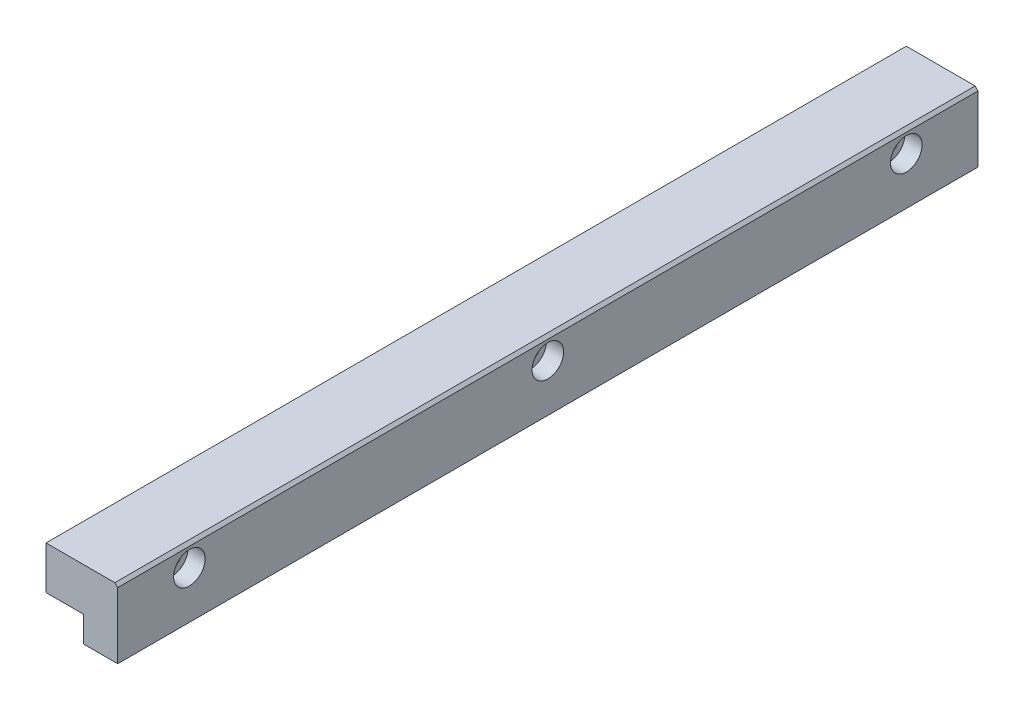
SolidWorks part; units mm, degrees
ref_plane "Front Plane" through (0, 0, 0) normal (0, 0, 1) x (1, 0, 0)
ref_plane "Top Plane" through (0, 0, 0) normal (0, 1, 0) x (1, 0, 0)
ref_plane "Right Plane" through (0, 0, 0) normal (1, 0, 0) x (0, 0, -1)
sketch "草图1" plane through (0, 0, 0) normal (0, 0, 1) x (1, 0, 0)
  line L1 (25, 440) -> (13, 440)
  line L2 (25, 440) -> (25, 465)
  line L3 (25, 465) -> (0, 465)
  line L4 (0, 450) -> (0, 465)
  line L8 (0, 450) -> (13, 450)
  line L9 (13, 440) -> (13, 450)
  dimension "D1" = 25
  dimension "D2" = 12
  dimension "D3" = 25
  dimension "D4" = 15
extrude "凸台-拉伸1" add sketch "草图1" against normal blind 300
hole_wizard "M6 凹头盖螺钉的柱形沉头孔1" positions "草图3" profile "草图2" counterbore size "M6" standard "Ansi Metric" end condition through all
sketch "草图3" plane through (25, 0, 0) normal (1, 0, 0) x (0, 0, -1)
  line L0 (300, 465) -> (0, 465) construction
  line L1 (0, 440) -> (0, 465) construction
  line L2 (300, 440) -> (300, 465) construction
  point P0 (25, 457.5)
  point P3 (275, 457.5)
  point P5 (150, 457.5)
  dimension "D1" = 7.5
  dimension "D2" = 25
  dimension "D3" = 25
  dimension "D4" = 7.5
  dimension "D5" = 7.5
  dimension "D6" = 150
sketch "草图2" plane through (25, 457.5, -25) normal (0, 1, 0) x (0, 0, -1)
  line L0 (0, 0) -> (0, 25)
  line L1 (0, 25) -> (3.2, 25)
  line L3 (3.2, 25) -> (3.2, 6)
  line L4 (3.2, 6) -> (5.5, 6)
  line L5 (5.5, 6) -> (5.5, 0)
  line L7 (5.5, 0) -> (0, 0)
  line L11 (0, -6.35) -> (0, 107.95) construction
  dimension "Í¨¿×¿×Ö±¾¶" = 6.4
  dimension "Í¨¿×¿×Éî¶È" = 25
  dimension "ÖùÐÎ³ÁÍ·¿×Ö±¾¶" = 11
  dimension "ÖùÐÎ³ÁÍ·¿×Éî¶È" = 6
chamfer "倒角1" distance 1 angle 45 4 edges at (25, 440, -150) (19, 440, -300) (13, 440, -150) (19, 440, 0)
chamfer "倒角2" distance 1 angle 45 1 edges at (25, 465, -150)
